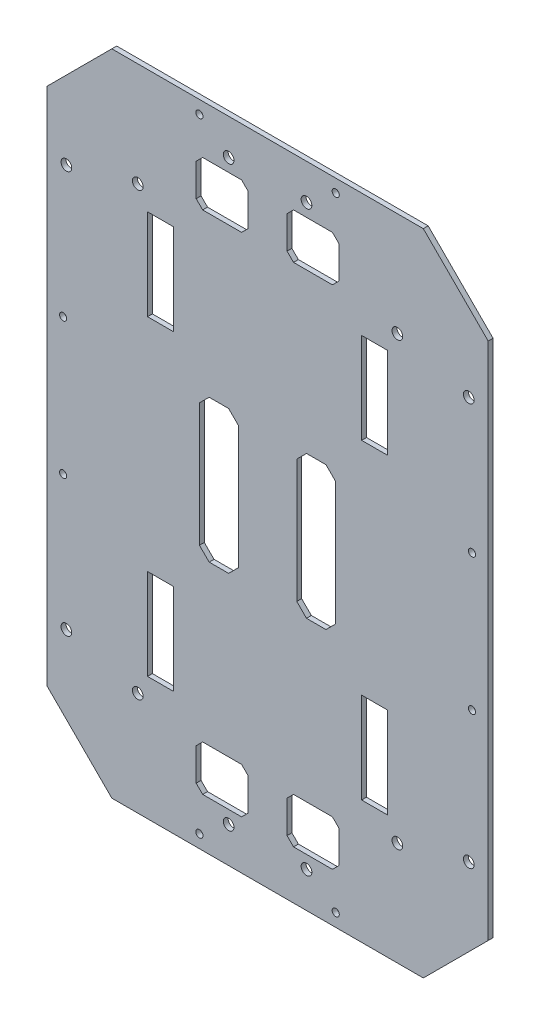
SolidWorks part; units mm, degrees
material "碳纤维板_1600kg_m3"
ref_plane "前视基准面" through (0, 0, 0) normal (0, 0, 1) x (1, 0, 0)
ref_plane "上视基准面" through (0, 0, 0) normal (0, 1, 0) x (1, 0, 0)
ref_plane "右视基准面" through (0, 0, 0) normal (1, 0, 0) x (0, 0, -1)
other "Configuration Table"
sketch "草图1" plane through (0, 0, 0) normal (0, 0, 1) x (1, 0, 0)
  line L586 (68, 80) -> (48, 100)
  line L587 (48, 100) -> (-48, 100)
  line L588 (-48, 100) -> (-68, 80)
  line L589 (-68, 80) -> (-68, -80)
  line L590 (-68, -80) -> (-48, -100)
  line L591 (-48, -100) -> (48, -100)
  line L592 (48, -100) -> (68, -80)
  line L593 (68, -80) -> (68, 80)
  line L594 (-37, -62) -> (-29, -62)
  line L595 (-29, -62) -> (-29, -34)
  line L596 (-29, -34) -> (-37, -34)
  line L597 (-37, -34) -> (-37, -62)
  line L598 (-20, -85) -> (-8, -85)
  line L599 (-8, -85) -> (-6, -83)
  line L600 (-6, -83) -> (-6, -73)
  line L601 (-6, -73) -> (-8, -71)
  line L602 (-8, -71) -> (-20, -71)
  line L603 (-20, -71) -> (-22, -73)
  line L604 (-22, -73) -> (-22, -83)
  line L605 (-22, -83) -> (-20, -85)
  line L606 (-37, 34) -> (-29, 34)
  line L607 (-29, 34) -> (-29, 62)
  line L608 (-29, 62) -> (-37, 62)
  line L609 (-37, 62) -> (-37, 34)
  line L610 (-20, 71) -> (-8, 71)
  line L611 (-8, 71) -> (-6, 73)
  line L612 (-6, 73) -> (-6, 83)
  line L613 (-6, 83) -> (-8, 85)
  line L614 (-8, 85) -> (-20, 85)
  line L615 (-20, 85) -> (-22, 83)
  line L616 (-22, 83) -> (-22, 73)
  line L617 (-22, 73) -> (-20, 71)
  line L618 (29, -62) -> (37, -62)
  line L619 (37, -62) -> (37, -34)
  line L620 (37, -34) -> (29, -34)
  line L621 (29, -34) -> (29, -62)
  line L622 (8, -85) -> (20, -85)
  line L623 (20, -85) -> (22, -83)
  line L624 (22, -83) -> (22, -73)
  line L625 (22, -73) -> (20, -71)
  line L626 (20, -71) -> (8, -71)
  line L627 (8, -71) -> (6, -73)
  line L628 (6, -73) -> (6, -83)
  line L629 (6, -83) -> (8, -85)
  line L630 (29, 34) -> (37, 34)
  line L631 (37, 34) -> (37, 62)
  line L632 (37, 62) -> (29, 62)
  line L633 (29, 62) -> (29, 34)
  line L634 (8, 71) -> (20, 71)
  line L635 (20, 71) -> (22, 73)
  line L636 (22, 73) -> (22, 83)
  line L637 (22, 83) -> (20, 85)
  line L638 (20, 85) -> (8, 85)
  line L639 (8, 85) -> (6, 83)
  line L640 (6, 83) -> (6, 73)
  line L641 (6, 73) -> (8, 71)
  line L642 (-18, -22) -> (-12, -22)
  line L643 (-12, -22) -> (-9, -19)
  line L644 (-9, -19) -> (-9, 19)
  line L645 (-9, 19) -> (-12, 22)
  line L646 (-12, 22) -> (-18, 22)
  line L647 (-18, 22) -> (-21, 19)
  line L648 (-21, 19) -> (-21, -19)
  line L649 (-21, -19) -> (-18, -22)
  line L650 (12, -22) -> (18, -22)
  line L651 (18, -22) -> (21, -19)
  line L652 (21, -19) -> (21, 19)
  line L653 (21, 19) -> (18, 22)
  line L654 (18, 22) -> (12, 22)
  line L655 (12, 22) -> (9, 19)
  line L656 (9, 19) -> (9, -19)
  line L657 (9, -19) -> (12, -22)
  circle A72 centre (-62, -62) radius 1.65
  circle A73 centre (-40, -68) radius 1.65
  circle A74 centre (-12, -89) radius 1.65
  circle A75 centre (-62, 62) radius 1.65
  circle A76 centre (-40, 68) radius 1.65
  circle A77 centre (-12, 89) radius 1.65
  circle A78 centre (62, -62) radius 1.65
  circle A79 centre (40, -68) radius 1.65
  circle A80 centre (12, -89) radius 1.65
  circle A81 centre (62, 62) radius 1.65
  circle A82 centre (40, 68) radius 1.65
  circle A83 centre (12, 89) radius 1.65
extrude "上层板和绑带槽" add sketch "草图1" along normal blind 1.5
sketch "草图3" plane through (0, 0, 0) normal (0, 0, 1) x (1, 0, 0)
  circle A0 centre (-63, -21) radius 1.1
  circle A1 centre (-21, -96) radius 1.1
  circle A2 centre (-63, 21) radius 1.1
  circle A3 centre (-21, 96) radius 1.1
  circle A4 centre (63, -21) radius 1.1
  circle A5 centre (21, -96) radius 1.1
  circle A6 centre (63, 21) radius 1.1
  circle A7 centre (21, 96) radius 1.1
extrude "八处板内钢索孔_无外伸耳" cut sketch "草图3" along normal blind 1.5
